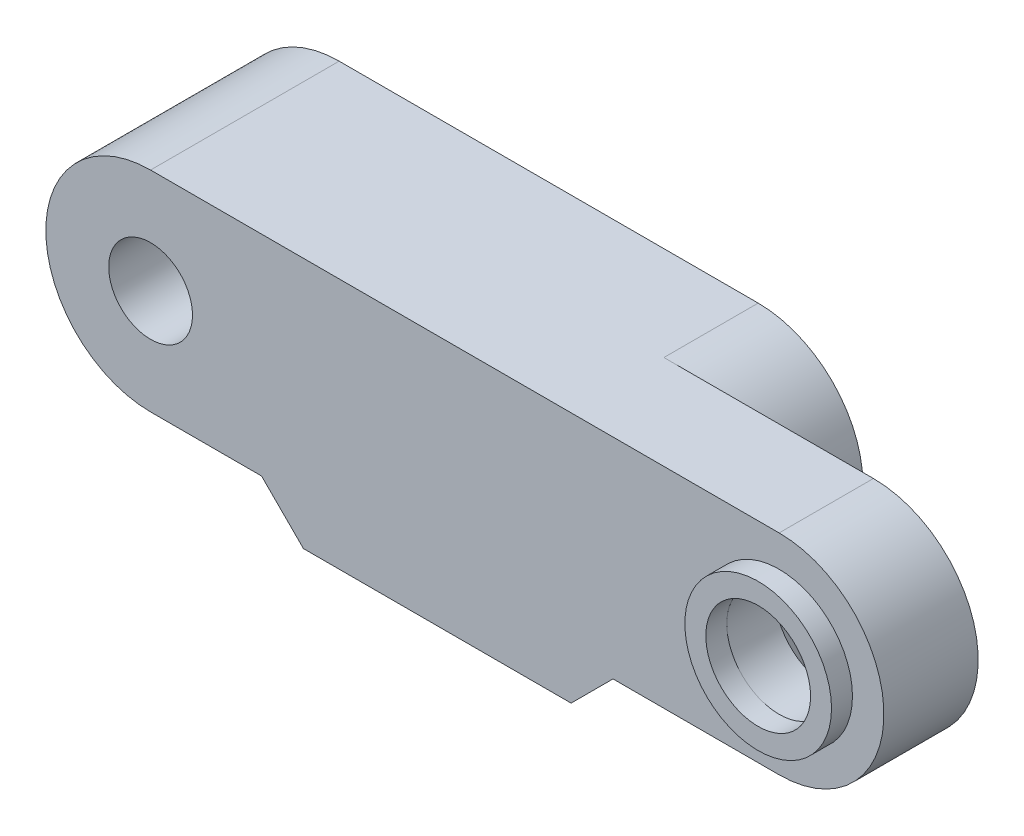
SolidWorks part; units mm, degrees
material "PET"
ref_plane "Přední rovina" through (0, 0, 0) normal (0, 0, 1) x (1, 0, 0)
ref_plane "Horní rovina" through (0, 0, 0) normal (0, 1, 0) x (1, 0, 0)
ref_plane "Pravá rovina" through (0, 0, 0) normal (1, 0, 0) x (0, 0, -1)
sketch "Skica1" plane through (0, 0, 0) normal (0, 0, 1) x (1, 0, 0)
  line L0 (0, 0) -> (30, 0) construction
  line L1 (0, 5) -> (30, 5)
  line L2 (0, -5) -> (30, -5)
  arc A0 (0, 5) -> (0, -5) centre (0, 0) ccw
  arc A1 (30, -5) -> (30, 5) centre (30, 0) ccw
  point P3 (15, 0)
  dimension "D1" = 30
  dimension "D2" = 10
extrude "Přidat vysunutím1" add sketch "Skica1" along normal blind 9
sketch "Skica2" plane through (0, 0, 9) normal (0, 0, 1) x (1, 0, 0)
  circle A0 centre (0, 0) radius 2
  circle A1 centre (30, 0) radius 2.55
  dimension "D1" = 4
  dimension "D2" = 5.1
extrude "Odebrat vysunutím1" cut sketch "Skica2" against normal blind 10
sketch "Skica4" plane through (0, 0, 0) normal (0, 0, -1) x (-1, 0, 0)
  line L0 (0, -5) -> (-30, -5) construction
  line L1 (-30, 5) -> (0, 5) construction
  line L2 (0, -5) -> (-20, -5)
  line L3 (-20, 5) -> (0, 5)
  arc A2 (-20, 5) -> (-20, -5) centre (-20, 0) ccw
  arc A3 (0, -5) -> (0, 5) centre (0, 0) ccw construction
  arc A4 (0, -5) -> (0, 5) centre (0, 0) ccw
  dimension "D1" = 20
  dimension "D2" = 5
extrude "Odebrat vysunutím5" cut sketch "Skica4" against normal blind 4.5 flip side to cut
sketch "Skica12" plane through (0, 0, 4.5) normal (0, 0, -1) x (-1, 0, 0)
  point P0 (-30, 0)
hole_wizard "Kuželové zahloubení pro M4 šroubu se zápustnou hlavou plochou1" positions "Skica12" profile "Skica13" countersink size "M4" standard "DIN"
sketch "Skica13" plane through (30, 0, 4.5) normal (1, 0, 0) x (0, 1, 0)
  line L0 (0, 0) -> (0, 14.8519)
  line L1 (0, 14.8519) -> (2.25, 13.5)
  line L2 (2.25, 13.5) -> (2.25, 2.45)
  line L3 (2.25, 2.45) -> (4.7, 0)
  line L5 (4.7, 0) -> (0, 0)
  line L6 (-2.25, 2.45) -> (-4.7, 0) construction
  line L10 (0, 14.8519) -> (-2.25, 13.5) construction
  line L11 (0, -6.35) -> (0, 107.95) construction
  dimension "Průměr díry" = 4.5
  dimension "Hloubka díry" = 13.5
  dimension "Průměr blíz. kuž. zahloubení" = 9.4
  dimension "Úhel blíz. kuž. zahloubení" = 90
  dimension "Úhel vrtání" = 118
sketch "Skica14" plane through (0, 0, 9) normal (0, 0, 1) x (1, 0, 0)
  circle A0 centre (30, 0) radius 3.5
  circle A1 centre (30, 0) radius 2.5
  dimension "D1" = 7
extrude "Přidat vysunutím3" add sketch "Skica14" along normal blind 1
sketch "Skica15" plane through (0, 0, 0) normal (0, 0, -1) x (-1, 0, 0)
  line L0 (-5.2956, 0) -> (-5.2956, -5)
  line L2 (0, -5) -> (-20, -5) construction
  line L3 (-25, 0) -> (-5.2956, 0)
  line L4 (-30, -5) -> (-20, -5) construction
  line L6 (-20.0711, -7) -> (-5.2956, -7)
  line L7 (-5.2956, -7) -> (-5.2956, -5)
  line L8 (-5.2956, -5) -> (-7.2956, -7)
  line L9 (-23.5355, -3.5355) -> (-20.0711, -7)
  circle A0 centre (0, 0) radius 5.2956 construction
  arc A1 (-20, 5) -> (-20, -5) centre (-20, 0) ccw construction
  arc A2 (-25, 0) -> (-23.5355, -3.5355) centre (-20, 0) ccw
  circle M4 centre (0, 0) radius 2
  arc M5 (-20, 5) -> (-20, -5) centre (-20, 0) ccw
  line M6 (-20, -5) -> (0, -5)
  arc M7 (0, -5) -> (0, 5) centre (0, 0) ccw
  line M8 (0, 5) -> (-20, 5)
  dimension "D1" = 45
  dimension "D2" = 45
  dimension "D3" = 14.7754
  dimension "D4" = 2
extrude "Přidat vysunutím5" add sketch "Skica15" against normal up to surface (9 mm away) contours L3 L0 M5 M6 M7 M8 M4 | L9 L6 L8 M5 M6 up to face at (33.5, 0, 9)
